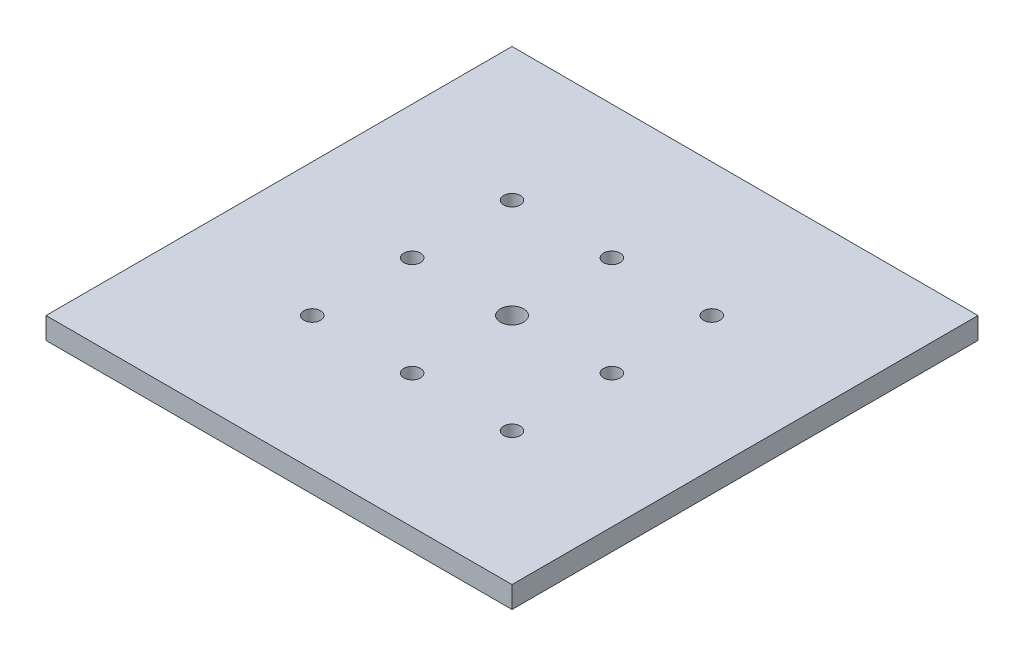
SolidWorks part; units mm, degrees
ref_plane "Alzado" through (0, 0, 0) normal (0, 0, 1) x (1, 0, 0)
ref_plane "Planta" through (0, 0, 0) normal (0, 1, 0) x (1, 0, 0)
ref_plane "Vista lateral" through (0, 0, 0) normal (1, 0, 0) x (0, 0, -1)
sketch "Croquis1" plane through (0, 0, 0) normal (0, 1, 0) x (1, 0, 0)
  line L0 (0, 110) -> (110, 0) construction
  line L1 (0, 0) -> (110, 0)
  line L2 (0, 0) -> (0, 110)
  line L3 (0, 110) -> (110, 110)
  line L4 (110, 0) -> (110, 110)
  line L6 (92.5, 17.5) -> (17.5, 17.5)
  line L7 (92.5, 17.5) -> (92.5, 92.5)
  line L8 (92.5, 92.5) -> (17.5, 92.5)
  line L9 (17.5, 17.5) -> (17.5, 92.5)
  line L10 (92.5, 17.5) -> (17.5, 92.5) construction
  line L11 (92.5, 92.5) -> (17.5, 17.5) construction
  point P4 (55, 55)
  dimension "D1" = 110
  dimension "D2" = 75
extrude "Saliente-Extruir1" add sketch "Croquis1" along normal blind 6.5
sketch "Croquis2" plane through (0, 6.5, 0) normal (0, 1, 0) x (1, 0, 0)
  line L0 (17.5, 92.5) -> (92.5, 17.5) construction
  line L2 (125, -15) -> (-15, -15)
  line L3 (125, -15) -> (125, 125)
  line L4 (125, 125) -> (-15, 125)
  line L5 (-15, -15) -> (-15, 125)
  line L6 (125, -15) -> (-15, 125) construction
  line L7 (125, 125) -> (-15, -15) construction
  line L8 (85, 25) -> (25, 25) construction
  line L9 (85, 25) -> (85, 85) construction
  line L10 (85, 85) -> (25, 85) construction
  line L11 (25, 25) -> (25, 85) construction
  line L12 (85, 25) -> (25, 85) construction
  line L13 (85, 85) -> (25, 25) construction
  circle A0 centre (55, 55) radius 3.5
  circle A1 centre (25, 85) radius 2.5
  circle A2 centre (85, 85) radius 2.5
  circle A3 centre (85, 25) radius 2.5
  circle A4 centre (25, 25) radius 2.5
  circle A5 centre (55, 85) radius 2.5
  circle A6 centre (85, 55) radius 2.5
  circle A7 centre (55, 25) radius 2.5
  circle A8 centre (25, 55) radius 2.5
  point P4 (55, 55)
  dimension "D2" = 7
  dimension "D3" = 5
  dimension "D6" = 4
  dimension "D1" = 140
  dimension "D4" = 60
  dimension "D5" = 4
extrude "Saliente-Extruir2" add sketch "Croquis2" along normal blind 6.5
